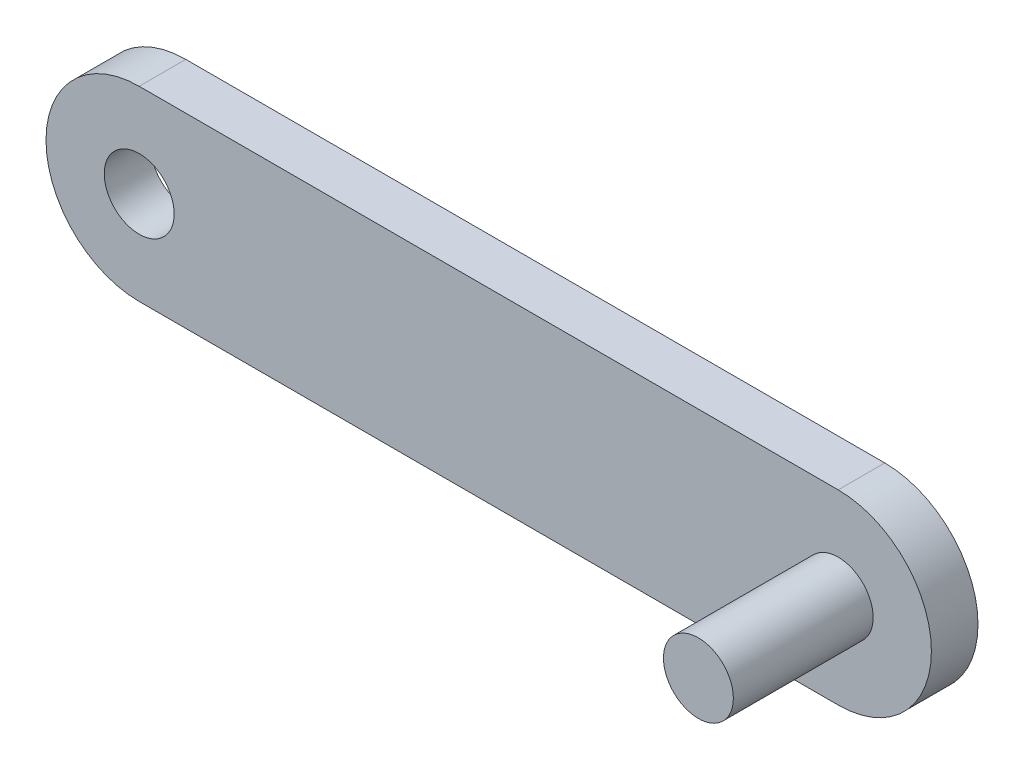
SolidWorks part; units mm, degrees
material "ABS"
ref_plane "Front Plane" through (0, 0, 0) normal (0, 0, 1) x (1, 0, 0)
ref_plane "Top Plane" through (0, 0, 0) normal (0, 1, 0) x (1, 0, 0)
ref_plane "Right Plane" through (0, 0, 0) normal (1, 0, 0) x (0, 0, -1)
sketch "Sketch1" plane through (0, 0, 0) normal (0, 0, 1) x (1, 0, 0)
  line L0 (0, 0) -> (30, 0) construction
  line L1 (0, 4) -> (30, 4)
  line L2 (0, -4) -> (30, -4)
  arc A0 (0, 4) -> (0, -4) centre (0, 0) ccw
  arc A1 (30, -4) -> (30, 4) centre (30, 0) ccw
  circle A2 centre (0, 0) radius 1.5
  point P3 (15, 0)
  dimension "D2" = 4
  dimension "D3" = 3
  dimension "D1" = 30
extrude "Boss-Extrude1" add sketch "Sketch1" along normal blind 2 contours L1 A1 L2 A0
sketch "Sketch2" plane through (0, 0, 2) normal (0, 0, 1) x (1, 0, 0)
  circle A0 centre (30, 0) radius 1.5
  dimension "D1" = 3
extrude "Boss-Extrude2" add sketch "Sketch2" along normal blind 6
